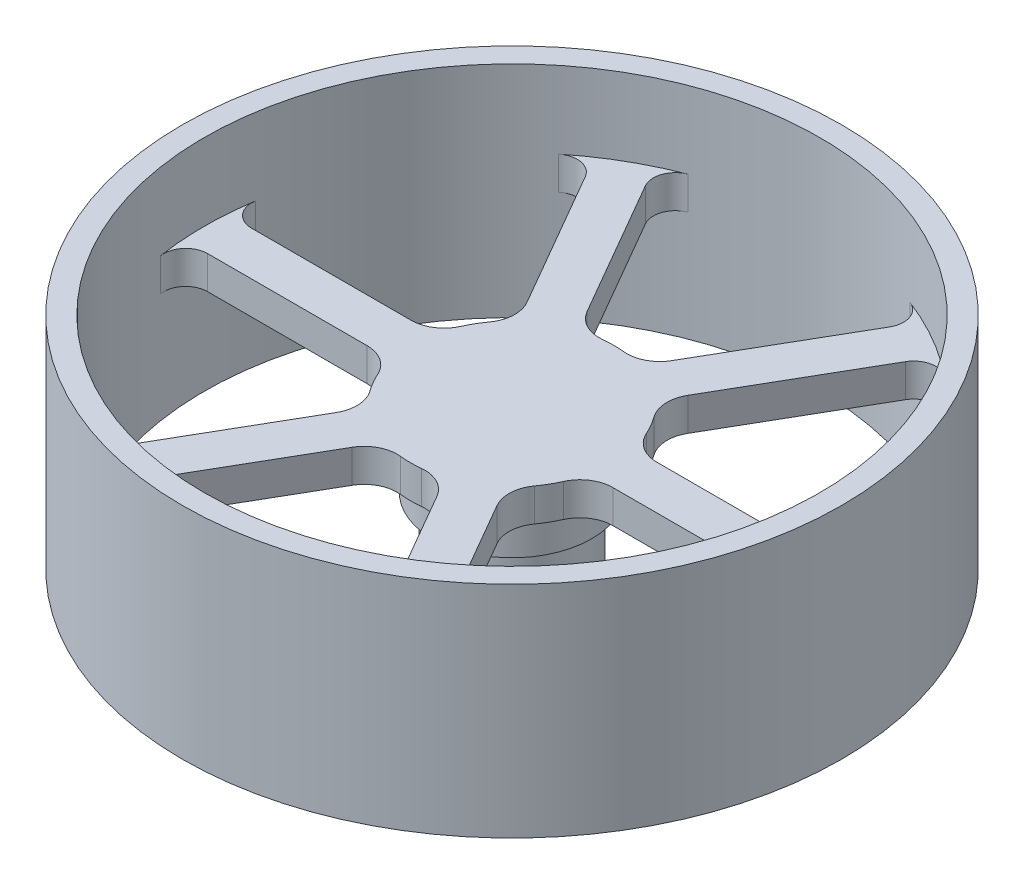
SolidWorks part; units mm, degrees
ref_plane "Front Plane" through (0, 0, 0) normal (0, 0, 1) x (1, 0, 0)
ref_plane "Top Plane" through (0, 0, 0) normal (0, 1, 0) x (1, 0, 0)
ref_plane "Right Plane" through (0, 0, 0) normal (1, 0, 0) x (0, 0, -1)
sketch "Sketch1" plane through (0, 0, 0) normal (0, 1, 0) x (1, 0, 0)
  circle A0 centre (0, 0) radius 30
  circle A1 centre (0, 0) radius 28
  dimension "D1" = 60
  dimension "D2" = 2
extrude "Boss-Extrude1" add sketch "Sketch1" along normal mid plane 20
sketch "Sketch2" plane through (0, 0, 0) normal (0, 1, 0) x (1, 0, 0)
  circle A0 centre (0, 0) radius 28
  circle A1 centre (0, 0) radius 28 construction
extrude "Boss-Extrude2" add sketch "Sketch2" along normal blind 3
sketch "Sketch3" plane through (0, 0, 0) normal (0, -1, 0) x (1, 0, 0)
  circle A0 centre (0, 0) radius 7.25
  dimension "D1" = 14.5
extrude "Boss-Extrude3" add sketch "Sketch3" along normal blind 4
sketch "Sketch4" plane through (0, -4, 0) normal (0, -1, 0) x (1, 0, 0)
  circle A0 centre (0, 0) radius 6
  dimension "D1" = 12
extrude "Boss-Extrude4" add sketch "Sketch4" along normal blind 11.7
sketch "Sketch5" plane through (0, -15.7, 0) normal (0, -1, 0) x (1, 0, 0)
  circle A0 centre (0, 0) radius 1.425
  dimension "D1" = 2.85
extrude "Cut-Extrude1" cut sketch "Sketch5" against normal blind 9
sketch "Sketch6" plane through (0, 0, 0) normal (0, -1, 0) x (1, 0, 0)
  line L0 (-3.625, 6.2787) -> (-12.75, 22.0836) construction
  line L1 (3.625, 6.2787) -> (12.75, 22.0836) construction
  line L2 (0, 7.25) -> (0, 4.04) construction
  line L3 (-3.625, 6.2787) -> (0, 0) construction
  line L4 (-3.8595, 10.6849) -> (-8.2084, 18.2174)
  line L5 (3.8595, 10.6849) -> (8.2084, 18.2174)
  line L6 (-2.7835, 8.8212) -> (-9.9753, 21.2778) construction
  line L7 (2.7835, 8.8212) -> (9.9753, 21.2778) construction
  line L8 (7.3236, 8.6849) -> (11.6725, 16.2174)
  line L9 (11.1831, 2) -> (19.8809, 2)
  line L10 (11.1831, -2) -> (19.8809, -2)
  line L11 (7.3236, -8.6849) -> (11.6725, -16.2174)
  line L12 (3.8595, -10.6849) -> (8.2084, -18.2174)
  line L13 (-3.8595, -10.6849) -> (-8.2084, -18.2174)
  line L14 (-7.3236, -8.6849) -> (-11.6725, -16.2174)
  line L15 (-11.1831, -2) -> (-19.8809, -2)
  line L16 (-11.1831, 2) -> (-19.8809, 2)
  line L17 (-7.3236, 8.6849) -> (-11.6725, 16.2174)
  circle A0 centre (0, 0) radius 7.25 construction
  circle A1 centre (0, 0) radius 28
  arc A3 (3.625, 6.2787) -> (-3.625, 6.2787) centre (0, 0) ccw construction
  circle A4 centre (0, 0) radius 7.25 construction
  arc A5 (6.4313, 22.6028) -> (-6.4313, 22.6028) centre (0, 0) ccw
  arc A6 (0.9525, 9.2008) -> (-0.9525, 9.2008) centre (0, 0) ccw
  arc A7 (2.7835, 8.8212) -> (-2.7835, 8.8212) centre (0, 0) ccw construction
  arc A8 (-3.8595, 10.6849) -> (-0.9525, 9.2008) centre (-1.2614, 12.1849) ccw
  arc A9 (0.9525, 9.2008) -> (3.8595, 10.6849) centre (1.2614, 12.1849) ccw
  arc A10 (9.9753, 21.2778) -> (-9.9753, 21.2778) centre (0, 0) ccw construction
  arc A11 (6.4313, 22.6028) -> (8.2084, 18.2174) centre (5.6103, 19.7174) cw
  arc A12 (-6.4313, 22.6028) -> (-8.2084, 18.2174) centre (-5.6103, 19.7174) ccw
  arc A13 (22.7903, 5.7317) -> (16.359, 16.8711) centre (0, 0) ccw
  arc A14 (16.359, 16.8711) -> (11.6725, 16.2174) centre (14.2706, 14.7174) ccw
  arc A15 (22.7903, 5.7317) -> (19.8809, 2) centre (19.8809, 5) cw
  arc A16 (7.3236, 8.6849) -> (7.4919, 5.4253) centre (9.9217, 7.1849) ccw
  arc A17 (8.4444, 3.7755) -> (7.4919, 5.4253) centre (0, 0) ccw
  arc A18 (8.4444, 3.7755) -> (11.1831, 2) centre (11.1831, 5) ccw
  arc A19 (16.359, -16.8711) -> (22.7903, -5.7317) centre (0, 0) ccw
  arc A20 (22.7903, -5.7317) -> (19.8809, -2) centre (19.8809, -5) ccw
  arc A21 (16.359, -16.8711) -> (11.6725, -16.2174) centre (14.2706, -14.7174) cw
  arc A22 (11.1831, -2) -> (8.4444, -3.7755) centre (11.1831, -5) ccw
  arc A23 (7.4919, -5.4253) -> (8.4444, -3.7755) centre (0, 0) ccw
  arc A24 (7.4919, -5.4253) -> (7.3236, -8.6849) centre (9.9217, -7.1849) ccw
  arc A25 (-6.4313, -22.6028) -> (6.4313, -22.6028) centre (0, 0) ccw
  arc A26 (6.4313, -22.6028) -> (8.2084, -18.2174) centre (5.6103, -19.7174) ccw
  arc A27 (-6.4313, -22.6028) -> (-8.2084, -18.2174) centre (-5.6103, -19.7174) cw
  arc A28 (3.8595, -10.6849) -> (0.9525, -9.2008) centre (1.2614, -12.1849) ccw
  arc A29 (-0.9525, -9.2008) -> (0.9525, -9.2008) centre (0, 0) ccw
  arc A30 (-0.9525, -9.2008) -> (-3.8595, -10.6849) centre (-1.2614, -12.1849) ccw
  arc A31 (-22.7903, -5.7317) -> (-16.359, -16.8711) centre (0, 0) ccw
  arc A32 (-16.359, -16.8711) -> (-11.6725, -16.2174) centre (-14.2706, -14.7174) ccw
  arc A33 (-22.7903, -5.7317) -> (-19.8809, -2) centre (-19.8809, -5) cw
  arc A34 (-7.3236, -8.6849) -> (-7.4919, -5.4253) centre (-9.9217, -7.1849) ccw
  arc A35 (-8.4444, -3.7755) -> (-7.4919, -5.4253) centre (0, 0) ccw
  arc A36 (-8.4444, -3.7755) -> (-11.1831, -2) centre (-11.1831, -5) ccw
  arc A37 (-16.359, 16.8711) -> (-22.7903, 5.7317) centre (0, 0) ccw
  arc A38 (-22.7903, 5.7317) -> (-19.8809, 2) centre (-19.8809, 5) ccw
  arc A39 (-16.359, 16.8711) -> (-11.6725, 16.2174) centre (-14.2706, 14.7174) cw
  arc A40 (-11.1831, 2) -> (-8.4444, 3.7755) centre (-11.1831, 5) ccw
  arc A41 (-7.4919, 5.4253) -> (-8.4444, 3.7755) centre (0, 0) ccw
  arc A42 (-7.4919, 5.4253) -> (-7.3236, 8.6849) centre (-9.9217, 7.1849) ccw
  arc A44 (12.75, 22.0836) -> (-12.75, 22.0836) centre (0, 0) ccw construction
  circle A46 centre (0, 0) radius 28
  point P92 (0, 0)
  dimension "D3" = 2
  dimension "D4" = 3
  dimension "D2" = 60
  dimension "D1" = 0
  dimension "D5" = 6
extrude "Cut-Extrude2" cut sketch "Sketch6" against normal blind 9 contours A5 A12 L4 A8 A6 A9 L5 A11 | A17 A18 L9 A15 A13 A14 L8 A16 | A23 A24 L11 A21 A19 A20 L10 A22 | A29 A30 L13 A27 A25 A26 L12 A28 | A35 A36 L15 A33 A31 A32 L14 A34 | A41 A42 L17 A39 A37 A38 L16 A40
sketch "Sketch7" plane through (0, 0, 0) normal (0, -1, 0) x (1, 0, 0)
  line L0 (8.2084, 18.2174) -> (11.1132, 23.2486)
  line L1 (-8.2084, 18.2174) -> (-11.1132, 23.2486)
  line L2 (-8.2084, 18.2174) -> (-3.8595, 10.6849) construction
  line L3 (11.6725, 16.2174) -> (14.5773, 21.2486)
  line L4 (19.8809, 2) -> (25.6905, 2)
  line L5 (19.8809, -2) -> (25.6905, -2)
  line L6 (11.6725, -16.2174) -> (14.5773, -21.2486)
  line L7 (8.2084, -18.2174) -> (11.1132, -23.2486)
  line L8 (-8.2084, -18.2174) -> (-11.1132, -23.2486)
  line L9 (-11.6725, -16.2174) -> (-14.5773, -21.2486)
  line L10 (-19.8809, -2) -> (-25.6905, -2)
  line L11 (-19.8809, 2) -> (-25.6905, 2)
  line L12 (-11.6725, 16.2174) -> (-14.5773, 21.2486)
  circle A0 centre (0, 0) radius 28 construction
  circle A1 centre (0, 0) radius 28 construction
  arc A2 (-6.4313, 22.6028) -> (-8.2084, 18.2174) centre (-5.6103, 19.7174) ccw construction
  circle A3 centre (0, 0) radius 28
  arc A5 (8.2084, 18.2174) -> (6.4313, 22.6028) centre (5.6103, 19.7174) ccw construction
  arc A6 (6.4313, 22.6028) -> (-6.4313, 22.6028) centre (0, 0) ccw construction
  arc A7 (-6.4313, 22.6028) -> (-8.2084, 18.2174) centre (-5.6103, 19.7174) ccw
  arc A8 (8.2084, 18.2174) -> (6.4313, 22.6028) centre (5.6103, 19.7174) ccw
  arc A9 (6.4313, 22.6028) -> (-6.4313, 22.6028) centre (0, 0) ccw
  arc A10 (11.1132, 23.2486) -> (10.1028, 26.1139) centre (9.3811, 24.2486) ccw
  arc A11 (-11.1132, 23.2486) -> (-10.1028, 26.1139) centre (-9.3811, 24.2486) cw
  arc A12 (19.8809, 2) -> (22.7903, 5.7317) centre (19.8809, 5) ccw
  arc A13 (22.7903, 5.7317) -> (16.359, 16.8711) centre (0, 0) ccw
  arc A14 (16.359, 16.8711) -> (11.6725, 16.2174) centre (14.2706, 14.7174) ccw
  arc A15 (14.5773, 21.2486) -> (17.5639, 21.8062) centre (16.3093, 20.2486) cw
  arc A16 (27.6667, 4.3077) -> (17.5639, 21.8062) centre (0, 0) ccw
  arc A17 (25.6905, 2) -> (27.6667, 4.3077) centre (25.6905, 4) ccw
  arc A18 (11.6725, -16.2174) -> (16.359, -16.8711) centre (14.2706, -14.7174) ccw
  arc A19 (16.359, -16.8711) -> (22.7903, -5.7317) centre (0, 0) ccw
  arc A20 (22.7903, -5.7317) -> (19.8809, -2) centre (19.8809, -5) ccw
  arc A21 (25.6905, -2) -> (27.6667, -4.3077) centre (25.6905, -4) cw
  arc A22 (17.5639, -21.8062) -> (27.6667, -4.3077) centre (0, 0) ccw
  arc A23 (14.5773, -21.2486) -> (17.5639, -21.8062) centre (16.3093, -20.2486) ccw
  arc A24 (-8.2084, -18.2174) -> (-6.4313, -22.6028) centre (-5.6103, -19.7174) ccw
  arc A25 (-6.4313, -22.6028) -> (6.4313, -22.6028) centre (0, 0) ccw
  arc A26 (6.4313, -22.6028) -> (8.2084, -18.2174) centre (5.6103, -19.7174) ccw
  arc A27 (11.1132, -23.2486) -> (10.1028, -26.1139) centre (9.3811, -24.2486) cw
  arc A28 (-10.1028, -26.1139) -> (10.1028, -26.1139) centre (0, 0) ccw
  arc A29 (-11.1132, -23.2486) -> (-10.1028, -26.1139) centre (-9.3811, -24.2486) ccw
  arc A30 (-19.8809, -2) -> (-22.7903, -5.7317) centre (-19.8809, -5) ccw
  arc A31 (-22.7903, -5.7317) -> (-16.359, -16.8711) centre (0, 0) ccw
  arc A32 (-16.359, -16.8711) -> (-11.6725, -16.2174) centre (-14.2706, -14.7174) ccw
  arc A33 (-14.5773, -21.2486) -> (-17.5639, -21.8062) centre (-16.3093, -20.2486) cw
  arc A34 (-27.6667, -4.3077) -> (-17.5639, -21.8062) centre (0, 0) ccw
  arc A35 (-25.6905, -2) -> (-27.6667, -4.3077) centre (-25.6905, -4) ccw
  arc A36 (-11.6725, 16.2174) -> (-16.359, 16.8711) centre (-14.2706, 14.7174) ccw
  arc A37 (-16.359, 16.8711) -> (-22.7903, 5.7317) centre (0, 0) ccw
  arc A38 (-22.7903, 5.7317) -> (-19.8809, 2) centre (-19.8809, 5) ccw
  arc A39 (-25.6905, 2) -> (-27.6667, 4.3077) centre (-25.6905, 4) cw
  arc A40 (-17.5639, 21.8062) -> (-27.6667, 4.3077) centre (0, 0) ccw
  arc A41 (-14.5773, 21.2486) -> (-17.5639, 21.8062) centre (-16.3093, 20.2486) ccw
  circle A44 centre (0, 0) radius 28
  point P16 (12.055, 25.2721)
  point P22 (-12.055, 25.2721)
  point P85 (0, 0)
  circle M18 centre (0, 0) radius 28
  arc M22 (-8.2084, 18.2174) -> (-6.4313, 22.6028) centre (-5.6103, 19.7174) cw
  arc M23 (-6.4313, 22.6028) -> (6.4313, 22.6028) centre (0, 0) cw
  arc M24 (6.4313, 22.6028) -> (8.2084, 18.2174) centre (5.6103, 19.7174) cw
  arc M30 (-19.8809, 2) -> (-22.7903, 5.7317) centre (-19.8809, 5) cw
  arc M31 (-22.7903, 5.7317) -> (-16.359, 16.8711) centre (0, 0) cw
  arc M32 (-16.359, 16.8711) -> (-11.6725, 16.2174) centre (-14.2706, 14.7174) cw
  arc M38 (11.6725, 16.2174) -> (16.359, 16.8711) centre (14.2706, 14.7174) cw
  arc M39 (16.359, 16.8711) -> (22.7903, 5.7317) centre (0, 0) cw
  arc M40 (22.7903, 5.7317) -> (19.8809, 2) centre (19.8809, 5) cw
  arc M46 (19.8809, -2) -> (22.7903, -5.7317) centre (19.8809, -5) cw
  arc M47 (22.7903, -5.7317) -> (16.359, -16.8711) centre (0, 0) cw
  arc M48 (16.359, -16.8711) -> (11.6725, -16.2174) centre (14.2706, -14.7174) cw
  arc M54 (-11.6725, -16.2174) -> (-16.359, -16.8711) centre (-14.2706, -14.7174) cw
  arc M55 (-16.359, -16.8711) -> (-22.7903, -5.7317) centre (0, 0) cw
  arc M56 (-22.7903, -5.7317) -> (-19.8809, -2) centre (-19.8809, -5) cw
  arc M62 (8.2084, -18.2174) -> (6.4313, -22.6028) centre (5.6103, -19.7174) cw
  arc M63 (6.4313, -22.6028) -> (-6.4313, -22.6028) centre (0, 0) cw
  arc M64 (-6.4313, -22.6028) -> (-8.2084, -18.2174) centre (-5.6103, -19.7174) cw
  dimension "D2" = 2
  dimension "D1" = 0
  dimension "D3" = 6
extrude "Cut-Extrude3" cut sketch "Sketch7" against normal blind 10 contours A11 L1 L0 A10 M22 M23 M24 M18 | L4 A17 A15 L3 M18 M38 M39 M40 | L6 A23 A21 L5 M18 M46 M47 M48 | L8 A29 A27 L7 M18 M62 M63 M64 | L10 A35 A33 L9 M18 M54 M55 M56 | L12 A41 A39 L11 M18 M30 M31 M32
